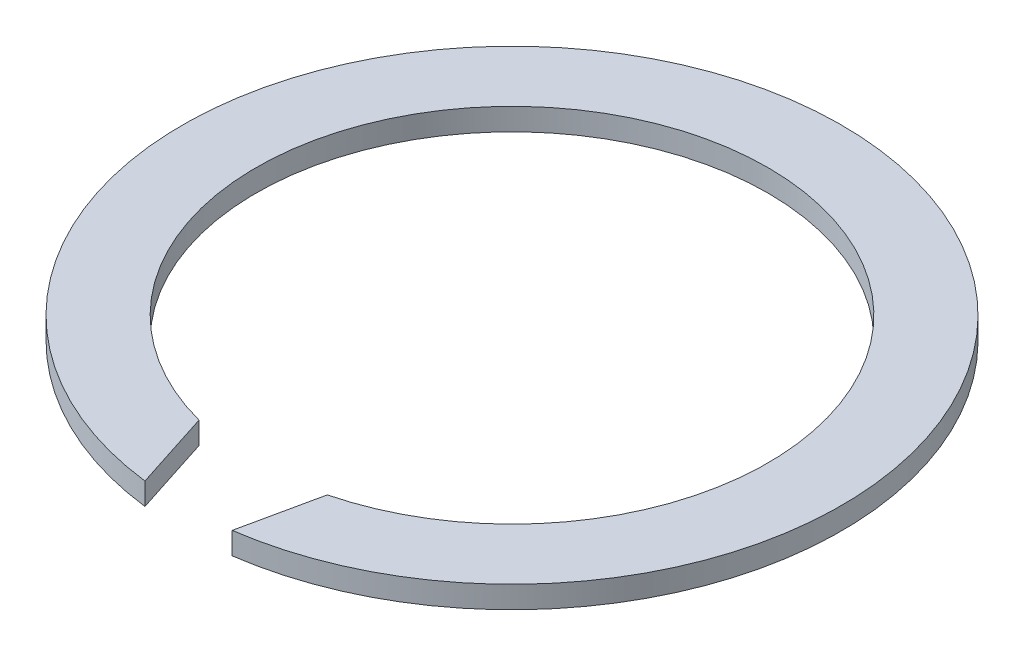
SolidWorks part; units mm, degrees
ref_plane "Спереди" through (0, 0, 0) normal (0, 0, 1) x (1, 0, 0)
ref_plane "Сверху" through (0, 0, 0) normal (0, 1, 0) x (1, 0, 0)
ref_plane "Справа" through (0, 0, 0) normal (1, 0, 0) x (0, 0, -1)
sketch "Эскиз1" plane through (0, 0, 0) normal (0, 1, 0) x (1, 0, 0)
  line L0 (-3.3099, -15.4765) -> (-1.9135, -19.8101)
  line L1 (3.6927, -15.5115) -> (2.7787, -19.7641)
  arc A0 (3.6927, -15.5115) -> (-3.3099, -15.4765) centre (0.2587, -2.0424) ccw
  arc A1 (2.7787, -19.7641) -> (-1.9135, -19.8101) centre (0.2587, -2.0424) ccw
  dimension "D1" = 27.8
  dimension "D2" = 35.8
extrude "Бобышка-Вытянуть1" add sketch "Эскиз1" along normal blind 1.2
